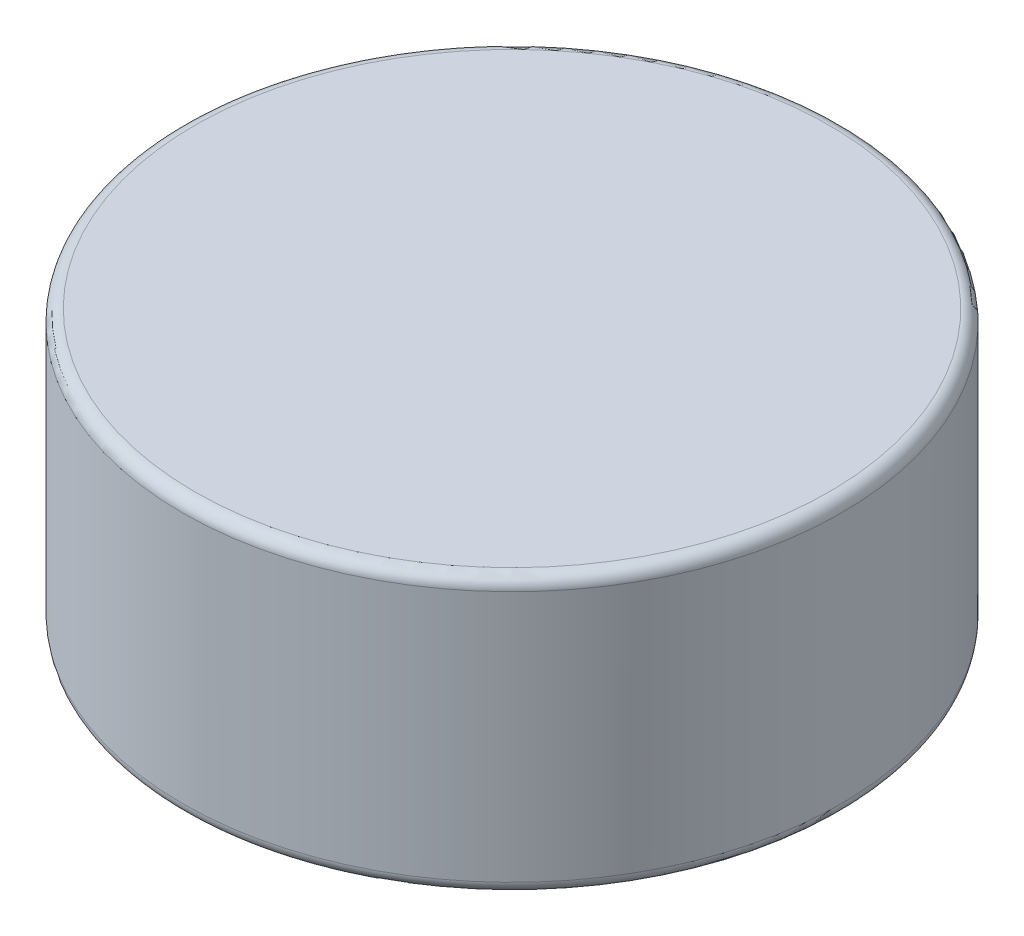
SolidWorks part; units mm, degrees
ref_plane "Front Plane" through (0, 0, 0) normal (0, 0, 1) x (1, 0, 0)
ref_plane "Top Plane" through (0, 0, 0) normal (0, 1, 0) x (1, 0, 0)
ref_plane "Right Plane" through (0, 0, 0) normal (1, 0, 0) x (0, 0, -1)
sketch "Sketch1" plane through (0, 0, 0) normal (1, 0, 0) x (0, 0, -1)
  line L0 (0, 30.9706) -> (0, -29.3569) construction
  line L1 (-11.5, -4.3195) -> (-11.5, 3.9913)
  line L2 (-11.5, 3.9913) -> (0, 3.9913)
  line L3 (0, 3.9913) -> (0, 6.9913)
  line L4 (0, 6.9913) -> (-13.5, 6.9913)
  line L5 (-13.5, 6.9913) -> (-13.5, -4.3195)
  line L6 (-13.5, -4.3195) -> (-11.5, -4.3195)
  dimension "D1" = 23
  dimension "D2" = 27
  dimension "D3" = 3
revolve "Revolve1" add sketch "Sketch1" angle 360 about L0
fillet "Fillet1" radius 0.5 2 edges at (0, -4.3195, 13.5) (0, 6.9913, 13.5)
